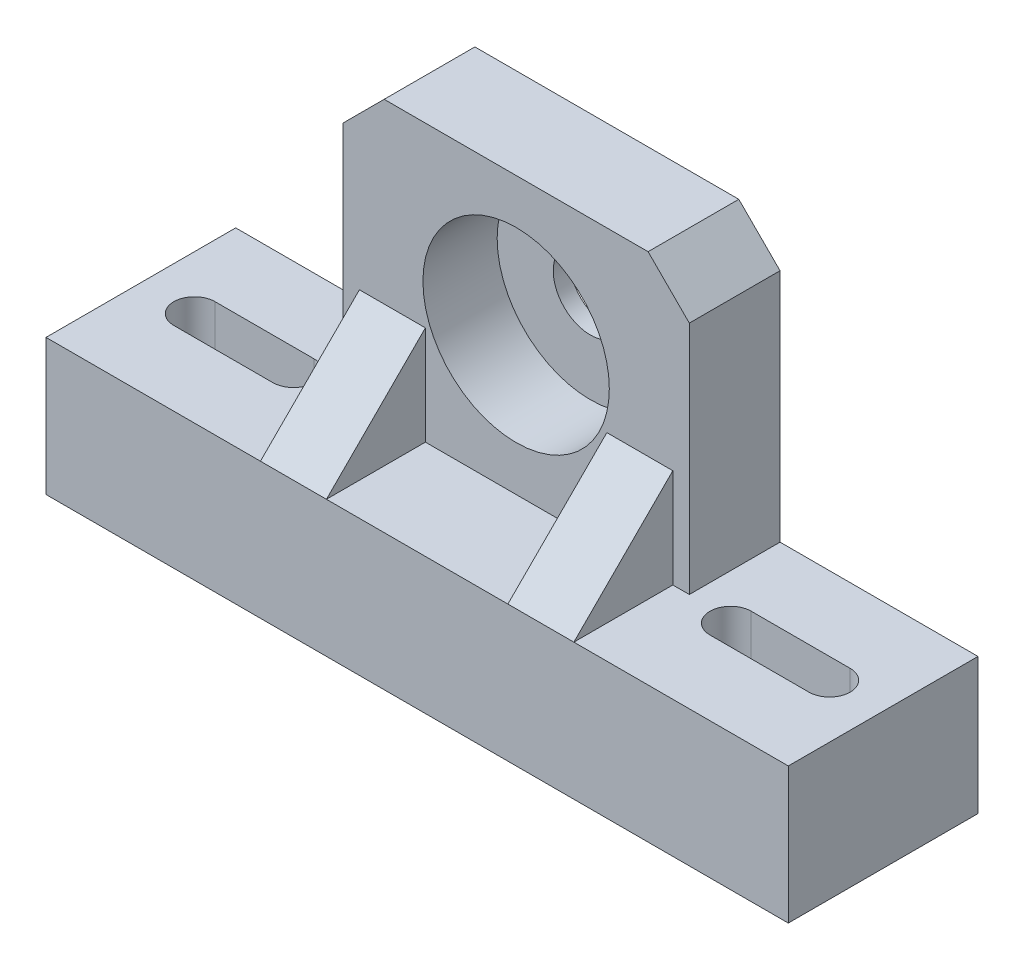
SolidWorks part; units mm, degrees
ref_plane "Alzado" through (0, 0, 0) normal (0, 0, 1) x (1, 0, 0)
ref_plane "Planta" through (0, 0, 0) normal (0, 1, 0) x (1, 0, 0)
ref_plane "Vista lateral" through (0, 0, 0) normal (1, 0, 0) x (0, 0, -1)
sketch "Croquis1" plane through (0, 0, 0) normal (0, 0, 1) x (1, 0, 0)
  line L0 (0, 11.3247) -> (0, -37.1547) construction
  line L1 (-21, -16.75) -> (21, -16.75)
  line L2 (-21, -16.75) -> (-21, 16.75)
  line L3 (-21, 16.75) -> (21, 16.75)
  line L4 (21, -16.75) -> (21, 16.75)
  line L5 (-21, -16.75) -> (21, 16.75) construction
  line L6 (-21, 16.75) -> (21, -16.75) construction
  line L7 (-45, -16.75) -> (45, -16.75)
  line L8 (-45, -16.75) -> (-45, -33.25)
  line L9 (-45, -33.25) -> (45, -33.25)
  line L10 (45, -16.75) -> (45, -33.25)
  point P0 (0, 0)
  point P12 (0, -33.25)
  dimension "D1" = 42
  dimension "D2" = 33.5
  dimension "D3" = 16.5
  dimension "D4" = 90
extrude "Saliente-Extruir1" add sketch "Croquis1" along normal mid plane 11 contours L1 L4 L3 L2 | L10 L7 L1 L8 L9
sketch "Croquis2" plane through (0, 0, 5.5) normal (0, 0, 1) x (1, 0, 0)
  line L1 (-45, -16.75) -> (45, -16.75)
  line L2 (-45, -16.75) -> (-45, -33.25)
  line L3 (-45, -33.25) -> (45, -33.25)
  line L4 (45, -16.75) -> (45, -33.25)
  line L8 (-21, 16.75) -> (-21, -16.75)
  line L9 (-21, -16.75) -> (-45, -16.75)
  line L10 (-45, -16.75) -> (-45, -33.25)
  line L11 (-45, -33.25) -> (45, -33.25)
  line L12 (45, -33.25) -> (45, -16.75)
  line L13 (45, -16.75) -> (21, -16.75)
  line L14 (21, -16.75) -> (21, 16.75)
  line L15 (21, 16.75) -> (-21, 16.75)
  line L16 (-21, 16.75) -> (-21, -16.75)
  line L17 (-21, -16.75) -> (-45, -16.75)
  line L18 (-45, -16.75) -> (-45, -33.25)
  line L19 (-45, -33.25) -> (45, -33.25)
  line L20 (45, -33.25) -> (45, -16.75)
  line L21 (45, -16.75) -> (21, -16.75)
  line L22 (21, -16.75) -> (21, 16.75)
  line L23 (21, 16.75) -> (-21, 16.75)
  line M14 (-21, -16.75) -> (-45, -16.75)
  line M15 (-45, -16.75) -> (-45, -33.25)
  line M16 (-45, -33.25) -> (45, -33.25)
  line M17 (45, -33.25) -> (45, -16.75)
  line M18 (45, -16.75) -> (21, -16.75)
  dimension "D1" = 0
extrude "Saliente-Extruir2" add sketch "Croquis2" along normal blind 12 contours L1 M14 M15 M16 M17 M18
ref_plane "Plano3" through (15, 0, 0) normal (1, 0, 0) x (0, 0, -1)
sketch "Croquis4" plane through (15, 0, 0) normal (1, 0, 0) x (0, 0, -1)
  line L0 (-5.5, -4.75) -> (-17.5, -16.75)
  line L1 (-5.5, -16.75) -> (-5.5, 16.75) construction
  line L2 (-17.5, -16.75) -> (5.5, -16.75) construction
  dimension "D1" = 45
rib "Nervio4" sketch "Croquis4" sketch "Croquis4" thickness 8 extrusion direction parallel to sketch draft on no parameters "D1"=8
mirror "Simetría1" about plane through (0, 0, 0) normal (1, 0, 0) of "Nervio4"
sketch "Croquis5" plane through (0, 0, 5.5) normal (0, 0, 1) x (1, 0, 0)
  circle A0 centre (0, 0) radius 4.5
  dimension "D1" = 9
extrude "Cortar-Extruir1" cut sketch "Croquis5" against normal blind 12
sketch "Croquis6" plane through (0, 0, 5.5) normal (0, 0, 1) x (1, 0, 0)
  circle A0 centre (0, 0) radius 11.3
  dimension "D1" = 22.6
extrude "Cortar-Extruir2" cut sketch "Croquis6" against normal blind 9
sketch "Croquis7" plane through (0, -33.25, 0) normal (0, -1, 0) x (1, 0, 0)
  line L0 (-45, 6) -> (45, 6) construction
  line L1 (-45, 17.5) -> (-45, -5.5) construction
  line L2 (45, 17.5) -> (45, -5.5) construction
  line L3 (-38.5, 6) -> (-26.5, 6) construction
  line L4 (-38.5, 8.5) -> (-26.5, 8.5)
  line L5 (-38.5, 3.5) -> (-26.5, 3.5)
  line L6 (-41, 12.981) -> (-41, -2.4001) construction
  line L7 (0, -16.6197) -> (0, 28.0899) construction
  line L8 (38.5, 6) -> (26.5, 6) construction
  line L9 (38.5, 8.5) -> (26.5, 8.5)
  line L10 (38.5, 3.5) -> (26.5, 3.5)
  arc A0 (-38.5, 8.5) -> (-38.5, 3.5) centre (-38.5, 6) ccw
  arc A1 (-26.5, 3.5) -> (-26.5, 8.5) centre (-26.5, 6) ccw
  arc A2 (38.5, 8.5) -> (38.5, 3.5) centre (38.5, 6) cw
  arc A3 (26.5, 3.5) -> (26.5, 8.5) centre (26.5, 6) cw
  point P8 (-32.5, 6)
  point P20 (32.5, 6)
  dimension "D1" = 5
  dimension "D2" = 4
  dimension "D3" = 12
extrude "Cortar-Extruir3" cut sketch "Croquis7" against normal through all
chamfer "Chaflán1" distance 5 angle 45 2 edges at (-21, 16.75, 0) (21, 16.75, 0)
